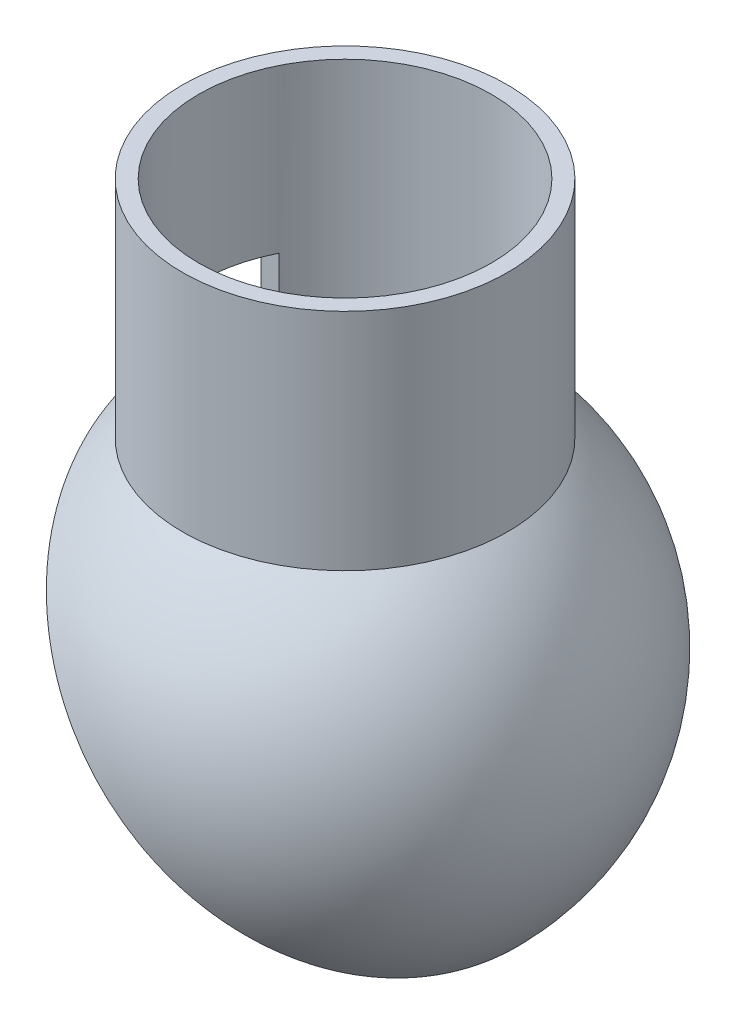
SolidWorks part; units mm, degrees
ref_plane "前视基准面" through (0, 0, 0) normal (0, 0, 1) x (1, 0, 0)
ref_plane "上视基准面" through (0, 0, 0) normal (0, 1, 0) x (1, 0, 0)
ref_plane "右视基准面" through (0, 0, 0) normal (1, 0, 0) x (0, 0, -1)
sketch "草图1" plane through (0, 0, 0) normal (0, 0, 1) x (1, 0, 0)
  line L4 (0, 25) -> (-10, 25)
  line L7 (-10, 25) -> (-10, 11.1803)
  line L9 (0, 25) -> (0, -15)
  arc A2 (-10, 11.1803) -> (0, -15) centre (0, 0) ccw
revolve "旋转2" add sketch "草图1" angle 360 about L9
sketch "草图4" plane through (0, 0, 0) normal (0, 0, 1) x (1, 0, 0)
  line L0 (0, 0) -> (-10.6066, 10.6066)
  line L1 (0, 0) -> (10.6066, -10.6066)
  arc A0 (-10, 11.1803) -> (10, 11.1803) centre (0, 0) ccw construction
  arc A1 (10.6066, -10.6066) -> (-10.6066, 10.6066) centre (0, 0) cw
extrude "切除-拉伸1" cut sketch "草图4" against normal through all and the other way through all contours A1 L1 L0
ref_plane "基准面4" through (0, 25, 0) normal (0, 1, 0) x (1, 0, 0)
sketch "草图5" plane through (0, 25, 0) normal (0, 1, 0) x (1, 0, 0)
  circle A0 centre (0, 0) radius 9
extrude "切除-拉伸2" cut sketch "草图5" against normal blind 15
sketch "草图6" plane through (0, 0, 0) normal (1, 0, 0) x (0, 0, -1)
  line L1 (0, 12) -> (4, 12)
  line L2 (0, 12) -> (-4, 12)
  line L3 (4, 12) -> (4, 15)
  line L4 (4, 15) -> (-4, 15)
  line L5 (-4, 15) -> (-4, 12)
extrude "切除-拉伸3" cut sketch "草图6" against normal blind 14
